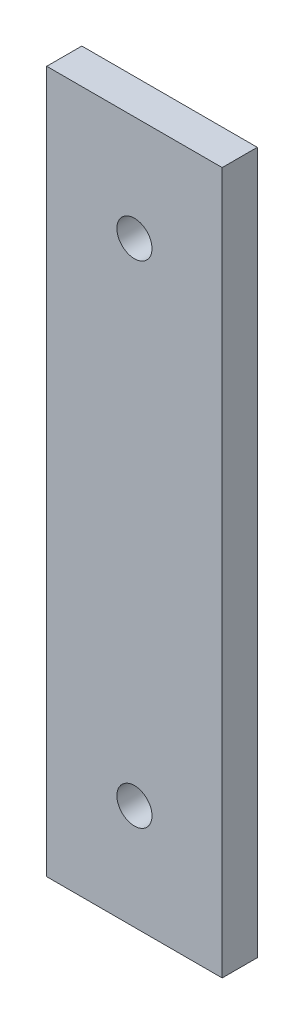
SolidWorks part; units mm, degrees
ref_plane "Front Plane" through (0, 0, 0) normal (0, 0, 1) x (1, 0, 0)
ref_plane "Top Plane" through (0, 0, 0) normal (0, 1, 0) x (1, 0, 0)
ref_plane "Right Plane" through (0, 0, 0) normal (1, 0, 0) x (0, 0, -1)
sketch "Sketch1" plane through (0, 0, 0) normal (0, 0, 1) x (1, 0, 0)
  line L1 (0, 65.1596) -> (25, 65.1596)
  line L2 (0, 65.1596) -> (0, -34.8404)
  line L3 (0, -34.8404) -> (25, -34.8404)
  line L4 (25, 65.1596) -> (25, -34.8404)
  dimension "D1" = 25
  dimension "D2" = 100
extrude "Boss-Extrude1" add sketch "Sketch1" along normal blind 5
sketch "Sketch2" plane through (0, 0, 5) normal (0, 0, 1) x (1, 0, 0)
  circle A0 centre (12.5, 50.1596) radius 2.5
  circle A1 centre (12.5, -19.8404) radius 2.5
  dimension "D3" = 5
  dimension "D4" = 5
extrude "Cut-Extrude1" cut sketch "Sketch2" against normal blind 10
